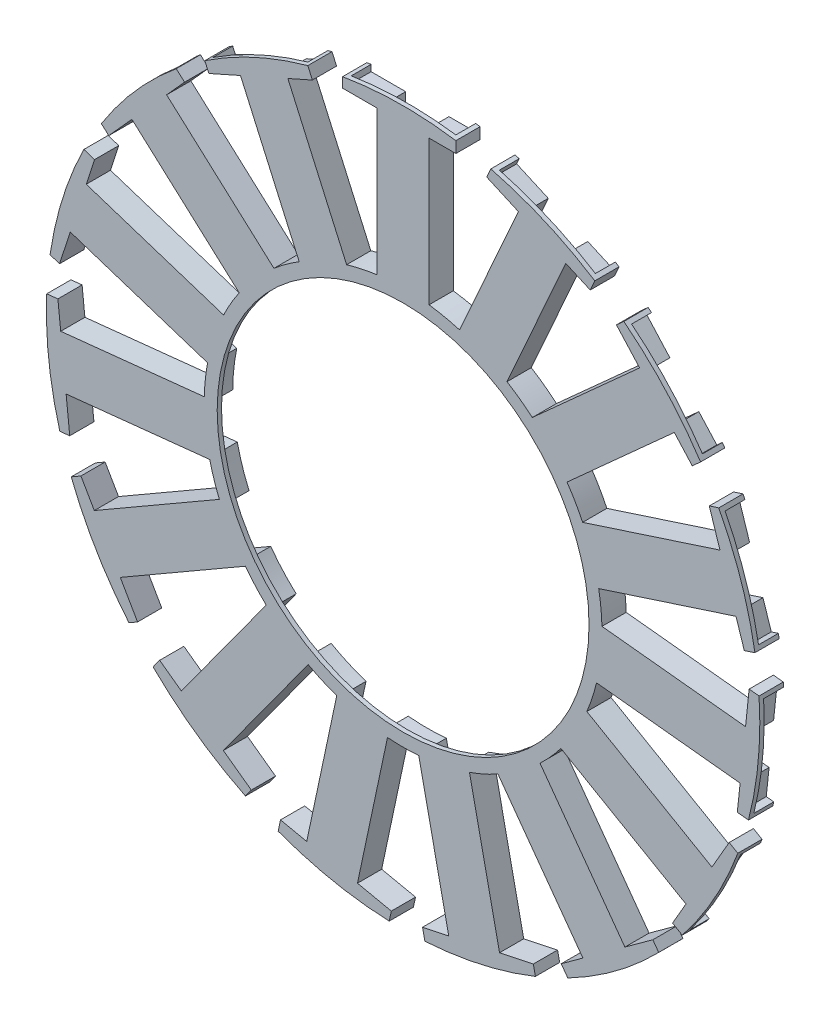
SolidWorks part; units mm, degrees
material "ABS"
ref_plane "正面" through (0, 0, 0) normal (0, 0, 1) x (1, 0, 0)
ref_plane "平面" through (0, 0, 0) normal (0, 1, 0) x (1, 0, 0)
ref_plane "右側面" through (0, 0, 0) normal (1, 0, 0) x (0, 0, -1)
sketch "ｽｹｯﾁ1" plane through (0, 0, 0) normal (0, 0, 1) x (1, 0, 0)
  line L0 (0, 0) -> (0, 40)
  line L1 (0, 0) -> (-2.5, 0)
  line L2 (-2.5, 0) -> (-2.5, 40)
  line L3 (0, 0) -> (2.5, 0)
  line L4 (2.5, 0) -> (2.5, 40)
  line L6 (-2.5, 40) -> (-6.5, 40)
  line L7 (2.5, 40) -> (5.6, 40)
  line L8 (5.6, 40) -> (5.6, 43.6422)
  line L9 (-6.5, 40) -> (-6.5, 43.5172)
  arc A1 (5.6, 43.6422) -> (-6.5, 43.5172) centre (0, 0) ccw
  circle A2 centre (0, 0) radius 22.5
  dimension "D2" = 88
  dimension "D3" = 45
  dimension "D4" = 2.5
  dimension "D5" = 2.5
  dimension "D7" = 6.5
  dimension "D8" = 5.6
extrude "ﾎﾞｽ - 押し出し2" add sketch "ｽｹｯﾁ1" along normal blind 2.3 contours L2 A2 L4 L3 L1
pattern_circular "円形ﾊﾟﾀｰﾝ2" count 15 over 360 about axis through (0, 0, 0) along (0, 0, 1) of "ﾎﾞｽ - 押し出し2"
sketch "ｽｹｯﾁ3" plane through (0, 0, 2.3) normal (0, 0, 1) x (1, 0, 0)
  circle A0 centre (0, 0) radius 3.25
  dimension "D1" = 6.5
extrude "ｶｯﾄ - 押し出し2" cut sketch "ｽｹｯﾁ3" against normal blind 3.2
sketch "ｽｹｯﾁ5" plane through (0, 0, 2.3) normal (0, 0, 1) x (1, 0, 0)
  line L0 (-15, 0) -> (15, 0)
  line L1 (0, 0) -> (0, -15.75)
  line L2 (-10.4775, -15.75) -> (10.4775, -15.75)
  circle A0 centre (-15, 0) radius 1.6
  circle A1 centre (15, 0) radius 1.6
  circle A2 centre (10.4775, -15.75) radius 1.6
  circle A3 centre (-10.4775, -15.75) radius 1.6
  point P5 (0, 0)
  point P11 (0, -15.75)
  point P17 (0, 17)
  dimension "D1" = 3.2
  dimension "D4" = 3.2
  dimension "D5" = 3.2
  dimension "D2" = 15.75
  dimension "D3" = 10.4775
extrude "ｶｯﾄ - 押し出し3" cut sketch "ｽｹｯﾁ5" against normal blind 10
sketch "ｽｹｯﾁ6" plane through (0, 0, 2.3) normal (0, 0, 1) x (1, 0, 0)
  line L0 (0, 0) -> (-16.6, 0)
  line L1 (-16.6, 0) -> (-16.6, 8)
  line L2 (0, 0) -> (0, 11.5739)
  line L3 (-16.6, 0) -> (-18.1, 0)
  line L4 (-18.1, 0) -> (-18.1, -8)
  circle A0 centre (-15, 0) radius 1.6 construction
  circle A1 centre (-16.6, 8) radius 1.6
  circle A5 centre (-18.1, -8) radius 1.6
  circle A6 centre (18.1, -8) radius 1.6
  circle A7 centre (16.6, 8) radius 1.6
  dimension "D2" = 3.2
  dimension "D5" = 3.2
  dimension "D1" = 8
  dimension "D3" = 1.5
  dimension "D4" = 8
  dimension "D6" = 16.6
extrude "ｶｯﾄ - 押し出し4" cut sketch "ｽｹｯﾁ6" against normal blind 10
shell "ｼｪﾙ2" thickness 0.5
sketch "ｽｹｯﾁ8" plane through (0, 0, 2.3) normal (0, 0, -1) x (-1, 0, 0)
  circle A0 centre (0, 0) radius 21.5
  dimension "D1" = 43
extrude "ｶｯﾄ - 押し出し6" cut sketch "ｽｹｯﾁ8" against normal blind 10 and the other way blind 10
sketch "ｽｹｯﾁ9" plane through (0, 0, 2.3) normal (0, 0, -1) x (-1, 0, 0)
  circle A0 centre (0, 0) radius 41.25
  circle A1 centre (0, 0) radius 60.0324
  dimension "D1" = 82.5
extrude "ｶｯﾄ - 押し出し7" cut sketch "ｽｹｯﾁ9" against normal blind 10 and the other way blind 10
